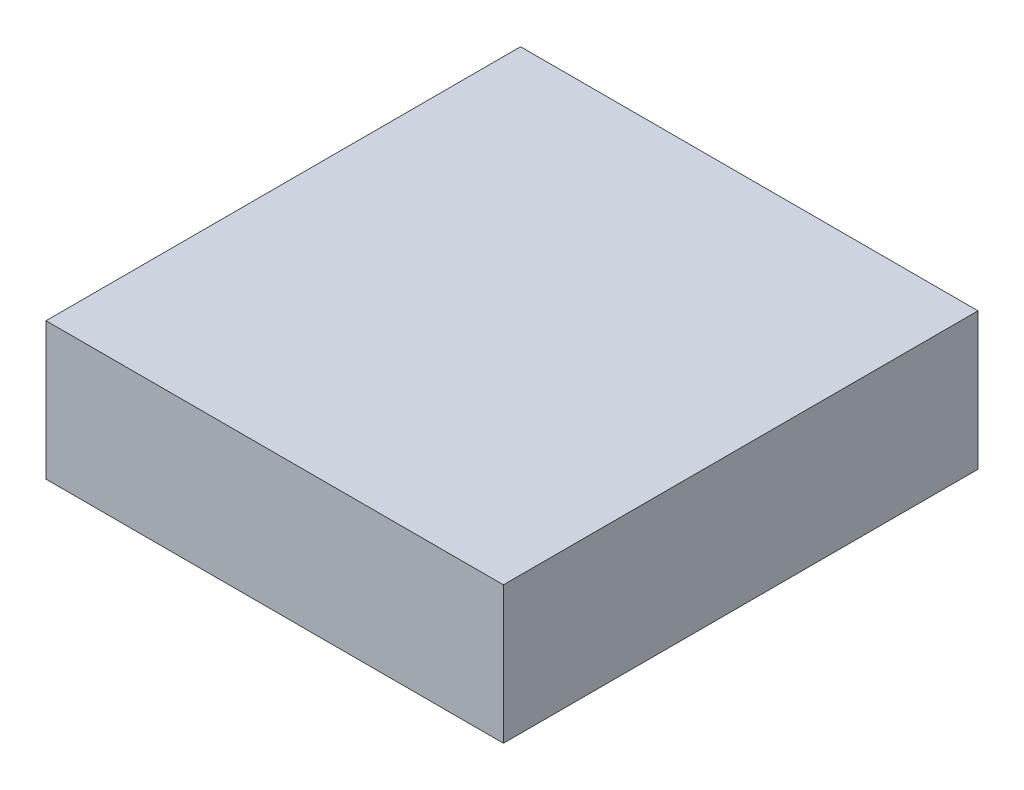
SolidWorks part; units mm, degrees
material "A-Glass Fiber"
ref_plane "Front Plane" through (0, 0, 0) normal (0, 0, 1) x (1, 0, 0)
ref_plane "Top Plane" through (0, 0, 0) normal (0, 1, 0) x (1, 0, 0)
ref_plane "Right Plane" through (0, 0, 0) normal (1, 0, 0) x (0, 0, -1)
sketch "Sketch1" plane through (0, 0, 0) normal (0, 1, 0) x (1, 0, 0)
  line L1 (-0.8, 0.83) -> (0.8, 0.83)
  line L2 (-0.8, 0.83) -> (-0.8, -0.83)
  line L3 (-0.8, -0.83) -> (0.8, -0.83)
  line L4 (0.8, 0.83) -> (0.8, -0.83)
  line L5 (-0.8, 0.83) -> (0.8, -0.83) construction
  line L6 (-0.8, -0.83) -> (0.8, 0.83) construction
  point P0 (0, 0)
  dimension "D1" = 1.6
  dimension "D2" = 1.66
extrude "Boss-Extrude1" add sketch "Sketch1" along normal blind 0.48
